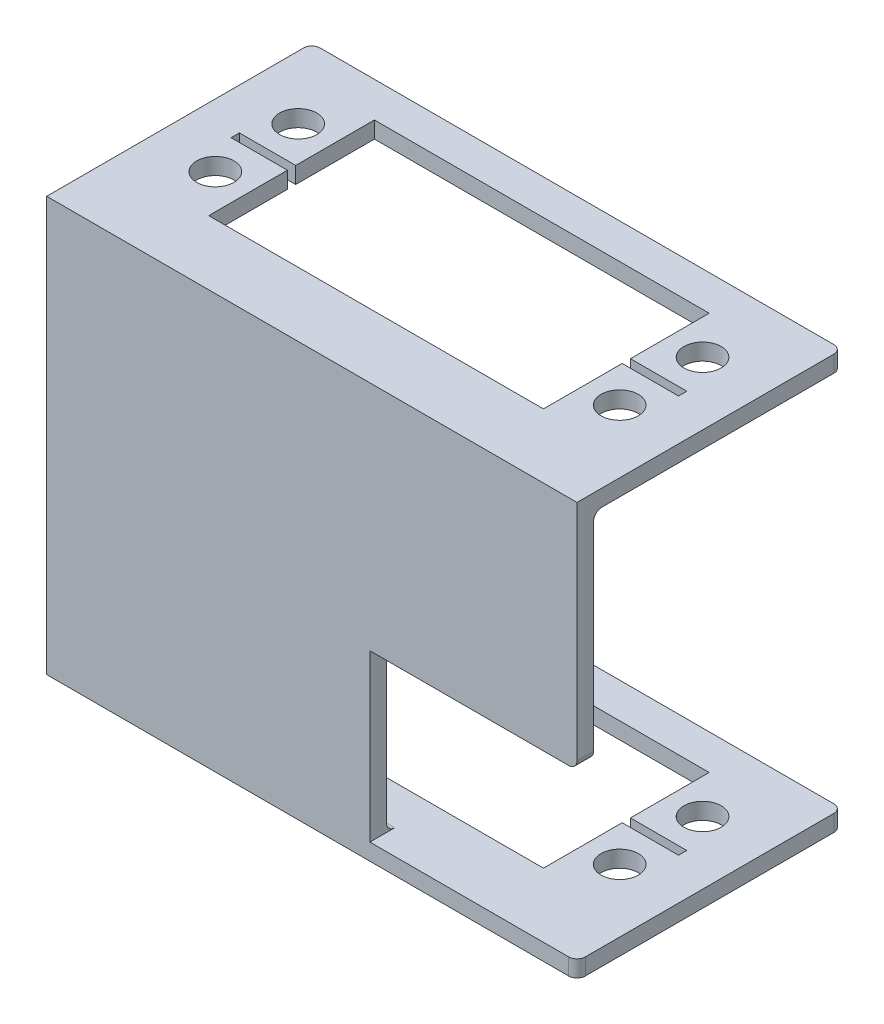
SolidWorks part; units mm, degrees
ref_plane "Front Plane" through (0, 0, 0) normal (0, 0, 1) x (1, 0, 0)
ref_plane "Top Plane" through (0, 0, 0) normal (0, 1, 0) x (1, 0, 0)
ref_plane "Right Plane" through (0, 0, 0) normal (1, 0, 0) x (0, 0, -1)
sketch "Sketch1" plane through (0, 0, 0) normal (0, 1, 0) x (1, 0, 0)
  line L1 (0, 0) -> (100, 0)
  line L2 (0, 0) -> (0, 32)
  line L3 (0, 32) -> (100, 32)
  line L4 (100, 0) -> (100, 32)
  dimension "D1" = 100
  dimension "D2" = 32
extrude "Boss-Extrude1" add sketch "Sketch1" along normal blind 2
sketch "Sketch2" plane through (0, 0, 0) normal (0, -1, 0) x (1, 0, 0)
  line L0 (0, -32) -> (0, 0) construction
  line L1 (100, 0) -> (0, 0)
  line L2 (100, 0) -> (100, -2)
  line L3 (100, -2) -> (0, -2)
  line L4 (0, 0) -> (0, -2)
  dimension "D1" = 2
extrude "Boss-Extrude2" add sketch "Sketch2" along normal blind 46
sketch "Sketch3" plane through (0, 0, 0) normal (0, 0, 1) x (1, 0, 0)
  line L1 (100, -46) -> (0, -46)
  line L2 (100, -46) -> (100, -48)
  line L3 (100, -48) -> (0, -48)
  line L4 (0, -46) -> (0, -48)
  dimension "D1" = 2
extrude "Boss-Extrude3" add sketch "Sketch3" against normal blind 32
sketch "Sketch4" plane through (0, 2, 0) normal (0, 1, 0) x (1, 0, 0)
  line L0 (0, 32) -> (0, 22.75)
  line L1 (0, 32) -> (0, 0) construction
  line L2 (0, 22.75) -> (7.6, 22.75)
  line L3 (7.6, 22.75) -> (7.6, 12.75)
  line L4 (7.6, 22.75) -> (11.8, 22.75)
  line L5 (11.8, 22.75) -> (11.8, 27.75)
  line L6 (7.6, 12.75) -> (11.8, 12.75)
  line L7 (11.8, 12.75) -> (11.8, 7.75)
  line L8 (11.8, 7.75) -> (11.8, 22.75)
  line L9 (11.8, 27.75) -> (52.2, 27.75)
  line L10 (52.2, 27.75) -> (52.2, 7.75)
  line L11 (52.2, 7.75) -> (11.8, 7.75)
  line L12 (7.6, 22.75) -> (56.4, 22.75)
  line L13 (7.6, 12.75) -> (56.4, 12.75)
  line L14 (7.6, 22.75) -> (7.6, 18.25)
  line L15 (11.8, 18.25) -> (5, 18.25)
  line L16 (5, 18.25) -> (5, 17.25)
  line L17 (5, 17.25) -> (11.8, 17.25)
  line L18 (52.2, 18.25) -> (59, 18.25)
  line L19 (52.2, 17.25) -> (59, 17.25)
  line L20 (59, 18.25) -> (59, 17.25)
  circle A0 centre (7.6, 22.75) radius 2.25
  circle A1 centre (7.6, 12.75) radius 2.25
  circle A2 centre (56.4, 12.75) radius 2.25
  circle A3 centre (56.4, 22.75) radius 2.25
  dimension "D1" = 4.2
  dimension "D2" = 6.8
  dimension "D3" = 6.8
  dimension "D4" = 6.8
extrude "Cut-Extrude1" cut sketch "Sketch4" against normal through all both and the other way through all
sketch "Sketch5" plane through (0, -48, 0) normal (0, -1, 0) x (1, 0, 0)
  line L0 (59, -17.75) -> (64, -17.75)
  line L1 (59, -18.25) -> (59, -17.25) construction
  line L3 (0, -32) -> (100, -32) construction
  line L4 (64, -32) -> (64, 0)
  line L5 (0, 0) -> (100, 0) construction
  line L7 (64, 0) -> (100, 0)
  line L9 (64, -32) -> (100, -32)
  line L10 (100, 0) -> (100, -32)
extrude "Cut-Extrude2" cut sketch "Sketch5" against normal through all both and the other way through all
sketch "Sketch6" plane through (0, 0, -2) normal (0, 0, -1) x (-1, 0, 0)
  line L1 (-64, -46) -> (-39, -46)
  line L2 (-64, -46) -> (-64, -26)
  line L3 (-64, -26) -> (-39, -26)
  line L4 (-39, -46) -> (-39, -26)
  dimension "D1" = 25
  dimension "D2" = 20
extrude "Cut-Extrude3" cut sketch "Sketch6" against normal blind 2
fillet "Fillet1" radius 1 8 edges at (0, 1, -32) (0, -47, -32) (64, -47, -32) (64, 1, -32) (32, 0, -2) (19.5, -46, -2) (64, -47, 0) (64, -26, -1)
